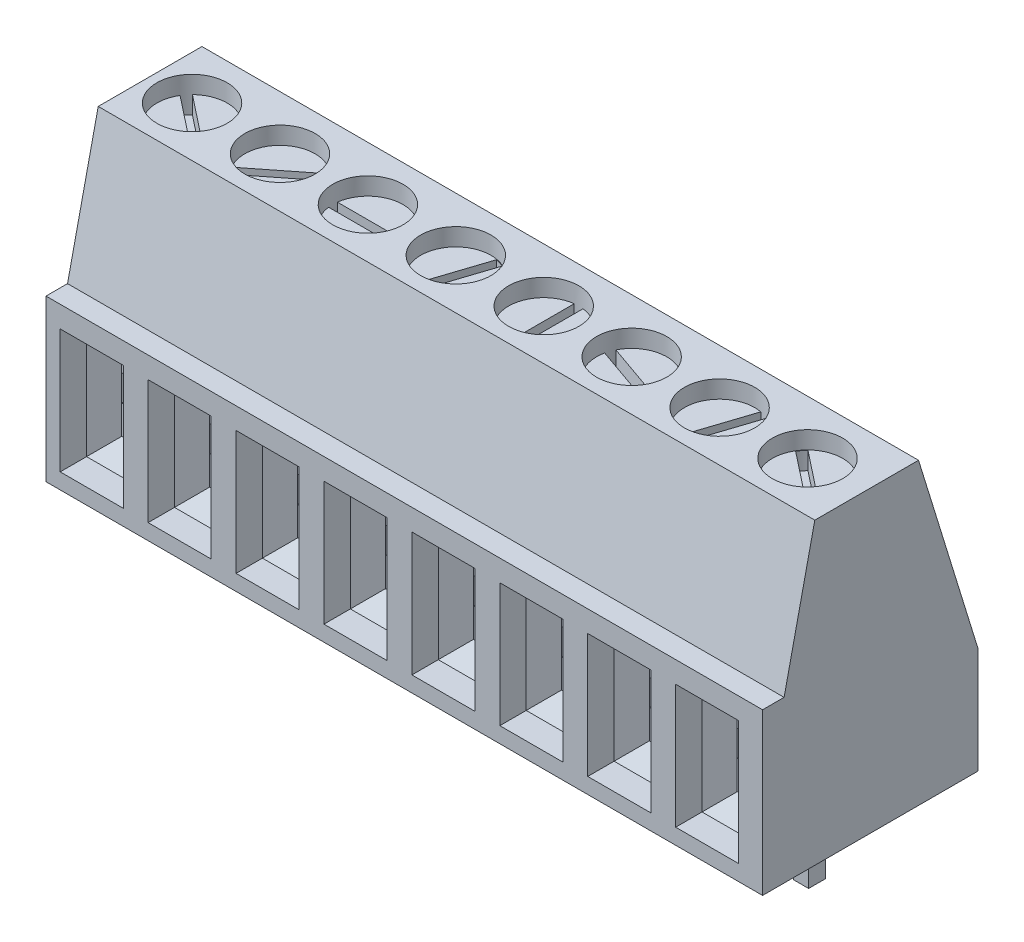
SolidWorks part; units mm, degrees
ref_plane "Front Plane" through (0, 0, 0) normal (0, 0, 1) x (1, 0, 0)
ref_plane "Top Plane" through (0, 0, 0) normal (0, 1, 0) x (1, 0, 0)
ref_plane "Right Plane" through (0, 0, 0) normal (1, 0, 0) x (0, 0, -1)
sketch "Sketch1" plane through (0, 0, 0) normal (0, 1, 0) x (1, 0, 0)
  line L1 (0, 0) -> (20.701, 0)
  line L2 (0, 0) -> (0, 6.223)
  line L3 (0, 6.223) -> (20.701, 6.223)
  line L4 (20.701, 0) -> (20.701, 6.223)
  dimension "D1" = 20.701
  dimension "D2" = 6.223
extrude "Extrude1" add sketch "Sketch1" along normal blind 8.636
sketch "Sketch2" plane through (20.701, 0, 0) normal (1, 0, 0) x (0, 0, -1)
  line L0 (-2.8691, 4.6459) -> (0.6218, 4.6459)
  line L1 (0.6218, 4.6459) -> (2.2176, 11.8272)
  line L2 (2.2176, 11.8272) -> (-2.8691, 11.8272)
  line L3 (-2.8691, 11.8272) -> (-2.8691, 4.6459)
extrude "Cut-Extrude1" cut sketch "Sketch2" against normal blind 25.4
sketch "Sketch3" plane through (20.701, 0, 0) normal (1, 0, 0) x (0, 0, -1)
  line L0 (4.013, 10.2314) -> (6.9054, 0.8558)
  line L1 (6.9054, 0.8558) -> (9.1994, 0.8558)
  line L2 (9.1994, 0.8558) -> (9.1994, 10.2314)
  line L3 (9.1994, 10.2314) -> (4.013, 10.2314)
extrude "Cut-Extrude2" cut sketch "Sketch3" against normal blind 25.4
sketch "Sketch4" plane through (0, 8.636, 0) normal (0, 1, 0) x (1, 0, 0)
  line L0 (0, 4.5051) -> (0, 1.5085) construction
  circle A0 centre (1.27, 2.9491) radius 1.016
  circle A1 centre (3.81, 2.9491) radius 1.016
  circle A2 centre (6.35, 2.9491) radius 1.016
  circle A3 centre (8.89, 2.9491) radius 1.016
  circle A4 centre (11.43, 2.9491) radius 1.016
  circle A5 centre (13.97, 2.9491) radius 1.016
  circle A6 centre (16.51, 2.9491) radius 1.016
  circle A7 centre (19.05, 2.9491) radius 1.016
  dimension "D1" = 1.27
extrude "Cut-Extrude3" cut sketch "Sketch4" against normal blind 0.508
sketch "Sketch5" plane through (0, 8.128, 0) normal (0, 1, 0) x (1, 0, 0)
  line L8 (18.1734, 3.4782) -> (19.7694, 2.2205)
  line L9 (16.7061, 3.9541) -> (16.0726, 2.0233)
  line L10 (12.9692, 3.1653) -> (14.8868, 2.4932)
  line L11 (11.303, 3.9651) -> (11.303, 1.9331)
  line L12 (8.6939, 1.9441) -> (9.3274, 3.8749)
  line L13 (5.334, 2.8221) -> (7.366, 2.8221)
  line L14 (3.0906, 2.2205) -> (4.6866, 3.4782)
  line L15 (0.3934, 3.4782) -> (1.9894, 2.2205)
  line L16 (18.3306, 3.6777) -> (19.9266, 2.42)
  line L17 (16.9474, 3.8749) -> (16.3139, 1.9441)
  line L18 (13.0532, 3.405) -> (14.9708, 2.7329)
  line L19 (11.557, 3.9651) -> (11.557, 1.9331)
  line L20 (8.4526, 2.0233) -> (9.0861, 3.9541)
  line L21 (5.334, 3.0761) -> (7.366, 3.0761)
  line L22 (2.9334, 2.42) -> (4.5294, 3.6777)
  line L23 (0.5506, 3.6777) -> (2.1466, 2.42)
  circle A13 centre (1.27, 2.9491) radius 1.016
  circle A14 centre (3.81, 2.9491) radius 1.016
  circle A15 centre (6.35, 2.9491) radius 1.016
  circle A16 centre (8.89, 2.9491) radius 1.005
  circle A17 centre (11.43, 2.9491) radius 1.016
  circle A18 centre (13.97, 2.9491) radius 1.016
  circle A19 centre (16.51, 2.9491) radius 1.016
  circle A20 centre (19.05, 2.9491) radius 0.9996
  circle M1 centre (1.27, 2.9491) radius 1.016
extrude "Cut-Extrude4" cut sketch "Sketch5" against normal blind 0.508 contours L23 L15 M1 | L14 A14 L22 | L13 A15 L21 | L12 A16 L20 | L19 A17 L11 | L10 A18 L18 | L17 A19 L9 | L8 A20 L16
sketch "Sketch6" plane through (0, 0, 0) normal (0, 0, 1) x (1, 0, 0)
  line L0 (2.9501, 4.0288) -> (2.9501, 0.4524)
  line L1 (0.4101, 4.0288) -> (2.232, 4.0288)
  line L2 (0.4101, 4.0288) -> (0.4101, 0.4524)
  line L3 (0.4101, 0.4524) -> (2.232, 0.4524)
  line L4 (2.232, 4.0288) -> (2.232, 0.4524)
  line L5 (2.9501, 4.0288) -> (4.772, 4.0288)
  line L6 (4.772, 4.0288) -> (4.772, 0.4524)
  line L7 (2.9501, 0.4524) -> (4.772, 0.4524)
  line L8 (5.4901, 4.0288) -> (5.4901, 0.4524)
  line L9 (5.4901, 4.0288) -> (7.312, 4.0288)
  line L10 (7.312, 4.0288) -> (7.312, 0.4524)
  line L11 (5.4901, 0.4524) -> (7.312, 0.4524)
  line L12 (8.0301, 4.0288) -> (8.0301, 0.4524)
  line L13 (8.0301, 4.0288) -> (9.852, 4.0288)
  line L14 (9.852, 4.0288) -> (9.852, 0.4524)
  line L15 (8.0301, 0.4524) -> (9.852, 0.4524)
  line L16 (10.5701, 4.0288) -> (10.5701, 0.4524)
  line L17 (10.5701, 4.0288) -> (12.392, 4.0288)
  line L18 (12.392, 4.0288) -> (12.392, 0.4524)
  line L19 (10.5701, 0.4524) -> (12.392, 0.4524)
  line L20 (13.1101, 4.0288) -> (13.1101, 0.4524)
  line L21 (13.1101, 4.0288) -> (14.932, 4.0288)
  line L22 (14.932, 4.0288) -> (14.932, 0.4524)
  line L23 (13.1101, 0.4524) -> (14.932, 0.4524)
  line L24 (15.6501, 4.0288) -> (15.6501, 0.4524)
  line L25 (15.6501, 4.0288) -> (17.472, 4.0288)
  line L26 (17.472, 4.0288) -> (17.472, 0.4524)
  line L27 (15.6501, 0.4524) -> (17.472, 0.4524)
  line L28 (18.1901, 4.0288) -> (18.1901, 0.4524)
  line L29 (18.1901, 4.0288) -> (20.012, 4.0288)
  line L30 (20.012, 4.0288) -> (20.012, 0.4524)
  line L31 (18.1901, 0.4524) -> (20.012, 0.4524)
extrude "Cut-Extrude5" cut sketch "Sketch6" against normal blind 1.27
chamfer "Chamfer1" distance 0.508 angle 45 32 edges at (20.012, 2.2406, -1.27) (19.1011, 0.4524, -1.27) (18.1901, 2.2406, -1.27) (19.1011, 4.0288, -1.27) (17.472, 2.2406, -1.27) (16.5611, 0.4524, -1.27) (15.6501, 2.2406, -1.27) (16.5611, 4.0288, -1.27) (14.932, 2.2406, -1.27) (14.0211, 0.4524, -1.27) (13.1101, 2.2406, -1.27) (14.0211, 4.0288, -1.27) (12.392, 2.2406, -1.27) (11.4811, 0.4524, -1.27) (10.5701, 2.2406, -1.27) (11.4811, 4.0288, -1.27) (9.852, 2.2406, -1.27) (8.9411, 0.4524, -1.27) (8.0301, 2.2406, -1.27) (8.9411, 4.0288, -1.27) (7.312, 2.2406, -1.27) (6.4011, 0.4524, -1.27) (5.4901, 2.2406, -1.27) (6.4011, 4.0288, -1.27) (4.772, 2.2406, -1.27) (3.8611, 0.4524, -1.27) (2.9501, 2.2406, -1.27) (3.8611, 4.0288, -1.27) (1.3211, 4.0288, -1.27) (2.232, 2.2406, -1.27) (1.3211, 0.4524, -1.27) (0.4101, 2.2406, -1.27)
sketch "Sketch7" plane through (0, 0, -1.27) normal (0, 0, 1) x (1, 0, 0)
  line L0 (0.9181, 3.5208) -> (0.9181, 0.9604) construction
  line L1 (0.9181, 2.5517) -> (1.724, 2.5517)
  line L2 (0.9181, 2.5517) -> (0.9181, 1.7937)
  line L3 (0.9181, 1.7937) -> (1.724, 1.7937)
  line L4 (1.724, 2.5517) -> (1.724, 1.7937)
  line L5 (1.724, 0.9604) -> (1.724, 3.5208) construction
  line L6 (3.4581, 2.5517) -> (3.4581, 1.7937)
  line L7 (3.4581, 2.5517) -> (4.264, 2.5517)
  line L8 (4.264, 2.5517) -> (4.264, 1.7937)
  line L9 (3.4581, 1.7937) -> (4.264, 1.7937)
  line L10 (5.9981, 2.5517) -> (5.9981, 1.7937)
  line L11 (5.9981, 2.5517) -> (6.804, 2.5517)
  line L12 (6.804, 2.5517) -> (6.804, 1.7937)
  line L13 (5.9981, 1.7937) -> (6.804, 1.7937)
  line L14 (8.5381, 2.5517) -> (8.5381, 1.7937)
  line L15 (8.5381, 2.5517) -> (9.344, 2.5517)
  line L16 (9.344, 2.5517) -> (9.344, 1.7937)
  line L17 (8.5381, 1.7937) -> (9.344, 1.7937)
  line L18 (11.0781, 2.5517) -> (11.0781, 1.7937)
  line L19 (11.0781, 2.5517) -> (11.884, 2.5517)
  line L20 (11.884, 2.5517) -> (11.884, 1.7937)
  line L21 (11.0781, 1.7937) -> (11.884, 1.7937)
  line L22 (13.6181, 2.5517) -> (13.6181, 1.7937)
  line L23 (13.6181, 2.5517) -> (14.424, 2.5517)
  line L24 (14.424, 2.5517) -> (14.424, 1.7937)
  line L25 (13.6181, 1.7937) -> (14.424, 1.7937)
  line L26 (16.1581, 2.5517) -> (16.1581, 1.7937)
  line L27 (16.1581, 2.5517) -> (16.964, 2.5517)
  line L28 (16.964, 2.5517) -> (16.964, 1.7937)
  line L29 (16.1581, 1.7937) -> (16.964, 1.7937)
  line L30 (18.6981, 2.5517) -> (18.6981, 1.7937)
  line L31 (18.6981, 2.5517) -> (19.504, 2.5517)
  line L32 (19.504, 2.5517) -> (19.504, 1.7937)
  line L33 (18.6981, 1.7937) -> (19.504, 1.7937)
extrude "Cut-Extrude6" cut sketch "Sketch7" against normal blind 1.27
sketch "Sketch8" plane through (0, 0, 0) normal (0, -1, 0) x (1, 0, 0)
  line L0 (3.6128, -2.7447) -> (3.6128, -3.2358)
  line L1 (1.0728, -2.7447) -> (1.5062, -2.7447)
  line L2 (1.0728, -2.7447) -> (1.0728, -3.2358)
  line L3 (1.0728, -3.2358) -> (1.5062, -3.2358)
  line L4 (1.5062, -2.7447) -> (1.5062, -3.2358)
  line L5 (3.6128, -2.7447) -> (4.0462, -2.7447)
  line L6 (4.0462, -2.7447) -> (4.0462, -3.2358)
  line L7 (3.6128, -3.2358) -> (4.0462, -3.2358)
  line L8 (6.1528, -2.7447) -> (6.1528, -3.2358)
  line L9 (6.1528, -2.7447) -> (6.5862, -2.7447)
  line L10 (6.5862, -2.7447) -> (6.5862, -3.2358)
  line L11 (6.1528, -3.2358) -> (6.5862, -3.2358)
  line L12 (8.6928, -2.7447) -> (8.6928, -3.2358)
  line L13 (8.6928, -2.7447) -> (9.1262, -2.7447)
  line L14 (9.1262, -2.7447) -> (9.1262, -3.2358)
  line L15 (8.6928, -3.2358) -> (9.1262, -3.2358)
  line L16 (11.2328, -2.7447) -> (11.2328, -3.2358)
  line L17 (11.2328, -2.7447) -> (11.6662, -2.7447)
  line L18 (11.6662, -2.7447) -> (11.6662, -3.2358)
  line L19 (11.2328, -3.2358) -> (11.6662, -3.2358)
  line L20 (13.7728, -2.7447) -> (13.7728, -3.2358)
  line L21 (13.7728, -2.7447) -> (14.2062, -2.7447)
  line L22 (14.2062, -2.7447) -> (14.2062, -3.2358)
  line L23 (13.7728, -3.2358) -> (14.2062, -3.2358)
  line L24 (16.3128, -2.7447) -> (16.3128, -3.2358)
  line L25 (16.3128, -2.7447) -> (16.7462, -2.7447)
  line L26 (16.7462, -2.7447) -> (16.7462, -3.2358)
  line L27 (16.3128, -3.2358) -> (16.7462, -3.2358)
  line L28 (18.8528, -2.7447) -> (18.8528, -3.2358)
  line L29 (18.8528, -2.7447) -> (19.2862, -2.7447)
  line L30 (19.2862, -2.7447) -> (19.2862, -3.2358)
  line L31 (18.8528, -3.2358) -> (19.2862, -3.2358)
extrude "Extrude2" add sketch "Sketch8" along normal blind 1.905
